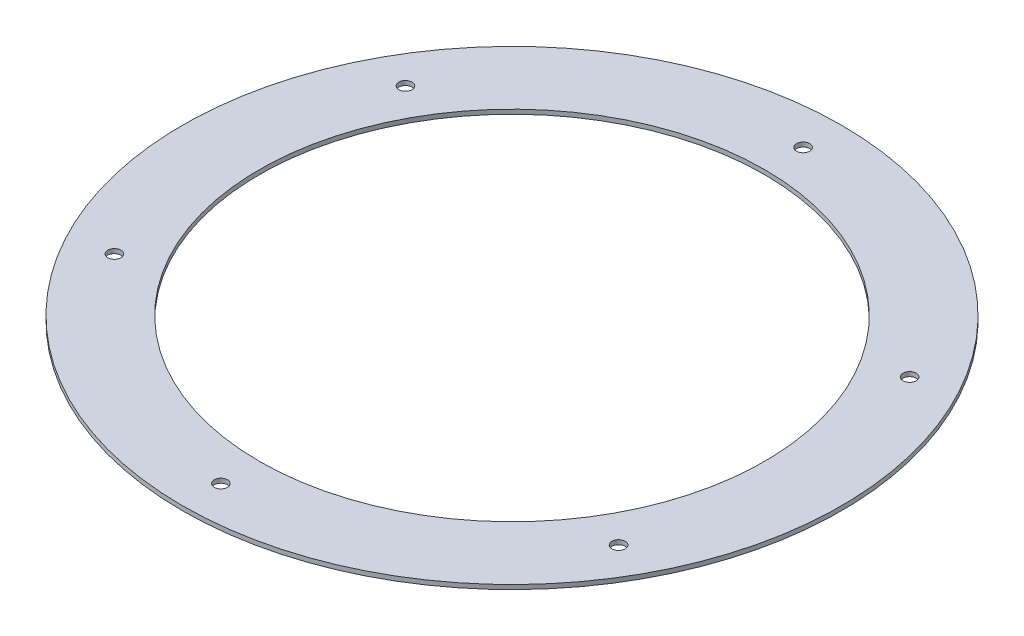
SolidWorks part; units mm, degrees
material "Rubber"
ref_plane "Front Plane" through (0, 0, 0) normal (0, 0, 1) x (1, 0, 0)
ref_plane "Top Plane" through (0, 0, 0) normal (0, 1, 0) x (1, 0, 0)
ref_plane "Right Plane" through (0, 0, 0) normal (1, 0, 0) x (0, 0, -1)
sketch "Sketch1" plane through (0, 0, 0) normal (0, 1, 0) x (1, 0, 0)
  line L0 (0, 132.5) -> (0, 150) construction
  line L1 (0, 132.5) -> (0, 115) construction
  circle A0 centre (0, 0) radius 150
  circle A1 centre (0, 0) radius 115
  circle A2 centre (0, 0) radius 132.5 construction
  circle A3 centre (0, 132.5) radius 3
  circle A4 centre (114.7484, 66.25) radius 3
  circle A5 centre (114.7484, -66.25) radius 3
  circle A6 centre (0, -132.5) radius 3
  circle A7 centre (-114.7484, -66.25) radius 3
  circle A8 centre (-114.7484, 66.25) radius 3
  point P21 (0, 0)
  dimension "D1" = 300
  dimension "D2" = 230
  dimension "D3" = 6
  dimension "D5" = 265
  dimension "D4" = 6
extrude "Boss-Extrude1" add sketch "Sketch1" along normal blind 2
